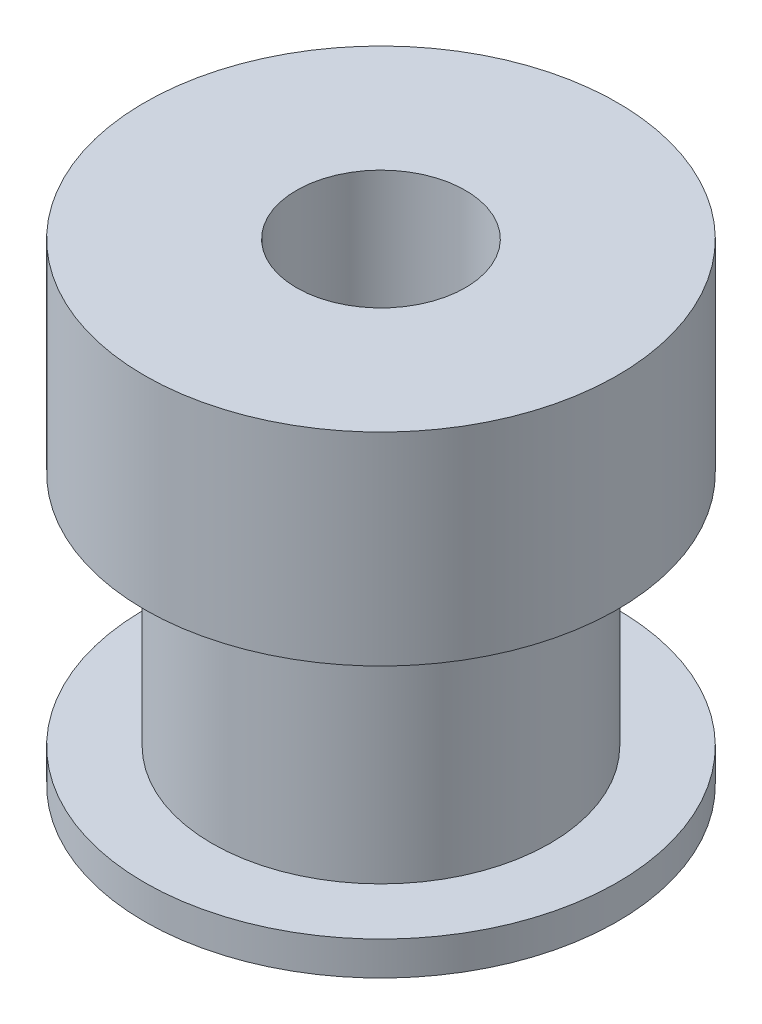
SolidWorks part; units mm, degrees
ref_plane "Front Plane" through (0, 0, 0) normal (0, 0, 1) x (1, 0, 0)
ref_plane "Top Plane" through (0, 0, 0) normal (0, 1, 0) x (1, 0, 0)
ref_plane "Right Plane" through (0, 0, 0) normal (1, 0, 0) x (0, 0, -1)
sketch "Sketch1" plane through (0, 0, 0) normal (0, 1, 0) x (1, 0, 0)
  circle A0 centre (0, 0) radius 7
extrude "Boss-Extrude1" add sketch "Sketch1" along normal blind 1
sketch "Sketch2" plane through (0, 1, 0) normal (0, 1, 0) x (1, 0, 0)
  circle A0 centre (0, 0) radius 5
extrude "Boss-Extrude2" add sketch "Sketch2" along normal blind 7
sketch "Sketch3" plane through (0, 8, 0) normal (0, 1, 0) x (1, 0, 0)
  circle A0 centre (0, 0) radius 7
extrude "Boss-Extrude3" add sketch "Sketch3" along normal blind 6
sketch "Sketch4" plane through (0, 14, 0) normal (0, 1, 0) x (1, 0, 0)
  circle A0 centre (0, 0) radius 2.5
extrude "Cut-Extrude1" cut sketch "Sketch4" against normal up to surface (14 mm away) up to face at (0, 0, 7)
